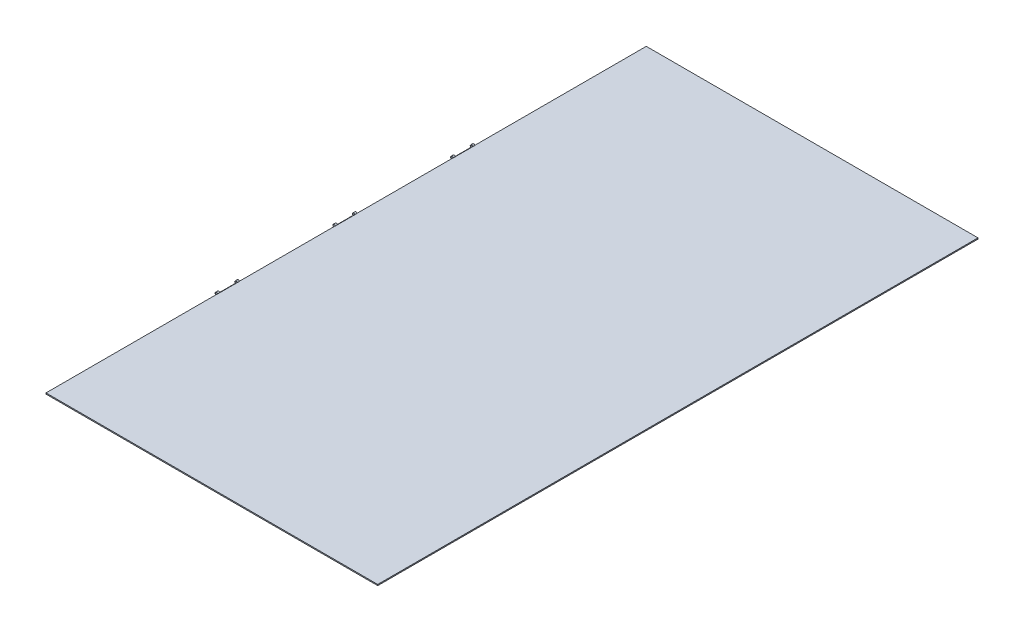
SolidWorks part; units mm, degrees
ref_plane "Front Plane" through (0, 0, 0) normal (0, 0, 1) x (1, 0, 0)
ref_plane "Top Plane" through (0, 0, 0) normal (0, 1, 0) x (1, 0, 0)
ref_plane "Right Plane" through (0, 0, 0) normal (1, 0, 0) x (0, 0, -1)
sketch "Sketch1" plane through (0, 0, 0) normal (0, 1, 0) x (1, 0, 0)
  line L1 (-760.75, 1376.6) -> (760.75, 1376.6)
  line L2 (-760.75, 1376.6) -> (-760.75, -1376.6)
  line L3 (-760.75, -1376.6) -> (760.75, -1376.6)
  line L4 (760.75, 1376.6) -> (760.75, -1376.6)
  line L5 (-760.75, 1376.6) -> (760.75, -1376.6) construction
  line L6 (-760.75, -1376.6) -> (760.75, 1376.6) construction
  point P0 (0, 0)
  dimension "D1" = 2753.2
  dimension "D2" = 1521.5
extrude "Boss-Extrude1" add sketch "Sketch1" along normal blind 5
sketch "Sketch4" plane through (0, 0, 0) normal (0, 0, 1) x (1, 0, 0)
  line L0 (-760.75, 5) -> (-760.75, 0) construction
  circle A0 centre (-765.75, 2.799) radius 5
  circle A1 centre (-765.75, 2.799) radius 6
  dimension "D1" = 10
  dimension "D2" = 12
extrude "Boss-Extrude3" add sketch "Sketch4" along normal mid plane 100
sketch "Sketch5" plane through (-760.75, 0, 0) normal (-1, 0, 0) x (0, 0, 1)
  line L0 (50, 8.799) -> (-50, 8.799) construction
  line L1 (40, -3.201) -> (-40, -3.201)
  line L2 (40, -3.201) -> (40, 8.799)
  line L3 (40, 8.799) -> (-40, 8.799)
  line L4 (-40, -3.201) -> (-40, 8.799)
  line L5 (40, -3.201) -> (-40, 8.799) construction
  line L6 (40, 8.799) -> (-40, -3.201) construction
  line L7 (-50, -3.201) -> (50, -3.201) construction
  point P0 (0, 2.799)
  point P7 (0, 0)
  point P10 (0, 0)
  dimension "D1" = 80
extrude "Cut-Extrude1" cut sketch "Sketch5" along normal blind 12
pattern_linear "LPattern1" count 2 spacing 540 along (0, 0, -1) of "Boss-Extrude3", "Cut-Extrude1"
pattern_linear "LPattern2" count 2 spacing 540 along (0, 0, 1) of "LPattern1", "Boss-Extrude3", "Cut-Extrude1"
